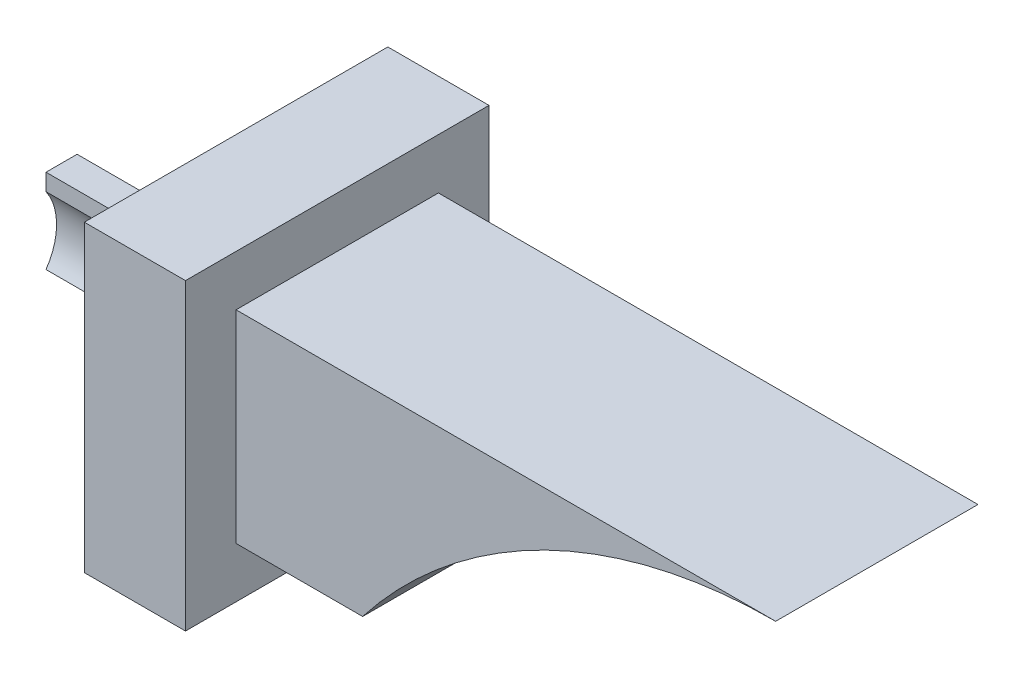
SolidWorks part; units mm, degrees
ref_plane "정면" through (0, 0, 0) normal (0, 0, 1) x (1, 0, 0)
ref_plane "윗면" through (0, 0, 0) normal (0, 1, 0) x (1, 0, 0)
ref_plane "우측면" through (0, 0, 0) normal (1, 0, 0) x (0, 0, -1)
sketch "스케치1" plane through (0, 0, 0) normal (0, 0, 1) x (1, 0, 0)
  line L0 (15.3555, 5.8707) -> (-16.6445, 5.8707)
  line L1 (-16.6445, 5.8707) -> (-16.6445, -6.1293)
  line L2 (-16.6445, -6.1293) -> (-9.1394, -6.1293)
  arc A0 (15.3555, 5.8707) -> (-9.1394, -6.1293) centre (15.3555, -25.1293) ccw
extrude "보스-돌출1" add sketch "스케치1" along normal blind 12
sketch "스케치2" plane through (-16.6445, 0, 0) normal (-1, 0, 0) x (0, 0, 1)
  line L0 (12, 5.8707) -> (12, -6.1293) construction
  line L1 (-3, -9.1293) -> (15, -9.1293)
  line L2 (-3, -9.1293) -> (-3, 8.8707)
  line L3 (-3, 8.8707) -> (15, 8.8707)
  line L4 (15, -9.1293) -> (15, 8.8707)
  line L5 (-3, -9.1293) -> (15, 8.8707) construction
  line L6 (-3, 8.8707) -> (15, -9.1293) construction
  line L7 (12, 5.8707) -> (0, 5.8707) construction
  point P0 (6, -0.1293)
  dimension "D1" = 6
  dimension "D2" = 6
  dimension "D3" = 18
  dimension "D4" = 18
extrude "보스-돌출2" add sketch "스케치2" along normal blind 6
sketch "스케치3" plane through (-22.6445, 0, 0) normal (-1, 0, 0) x (0, 0, 1)
  line L0 (5.4283, 1.5737) -> (5.4283, 2.5737)
  line L1 (5.4283, 2.5737) -> (7.2728, 2.5737)
  line L2 (5.4283, -2.4263) -> (7.2728, -2.4263)
  line L3 (6.3505, 3.5737) -> (6.3505, -8.3799) construction
  line L4 (7.2728, 1.5737) -> (7.2728, 2.5737)
  arc A0 (5.4283, -2.4263) -> (5.4283, 1.5737) centre (2.556, -0.4263) ccw
  arc A1 (7.2728, -2.4263) -> (7.2728, 1.5737) centre (10.145, -0.4263) cw
  point P8 (6.3505, -2.4263)
  point P11 (6.3505, 2.5737)
extrude "보스-돌출3" add sketch "스케치3" along normal blind 10
sketch "스케치5" plane through (0, 0, 12) normal (0, 0, 1) x (1, 0, 0)
  line L3 (15.3555, 5.8707) -> (-16.6445, 5.8707)
  line L4 (-16.6445, 5.8707) -> (-16.6445, -6.1293)
  line L5 (-16.6445, -6.1293) -> (-9.1394, -6.1293)
  line L6 (15.3555, 5.8707) -> (-16.6445, 5.8707)
  line L7 (-16.6445, 5.8707) -> (-16.6445, -6.1293)
  line L8 (-16.6445, -6.1293) -> (-9.1394, -6.1293)
  arc A1 (15.3555, 5.8707) -> (-9.1394, -6.1293) centre (15.3555, -25.1293) ccw
  arc A2 (15.3555, 5.8707) -> (-9.1394, -6.1293) centre (15.3555, -25.1293) ccw
  dimension "D1" = 0
